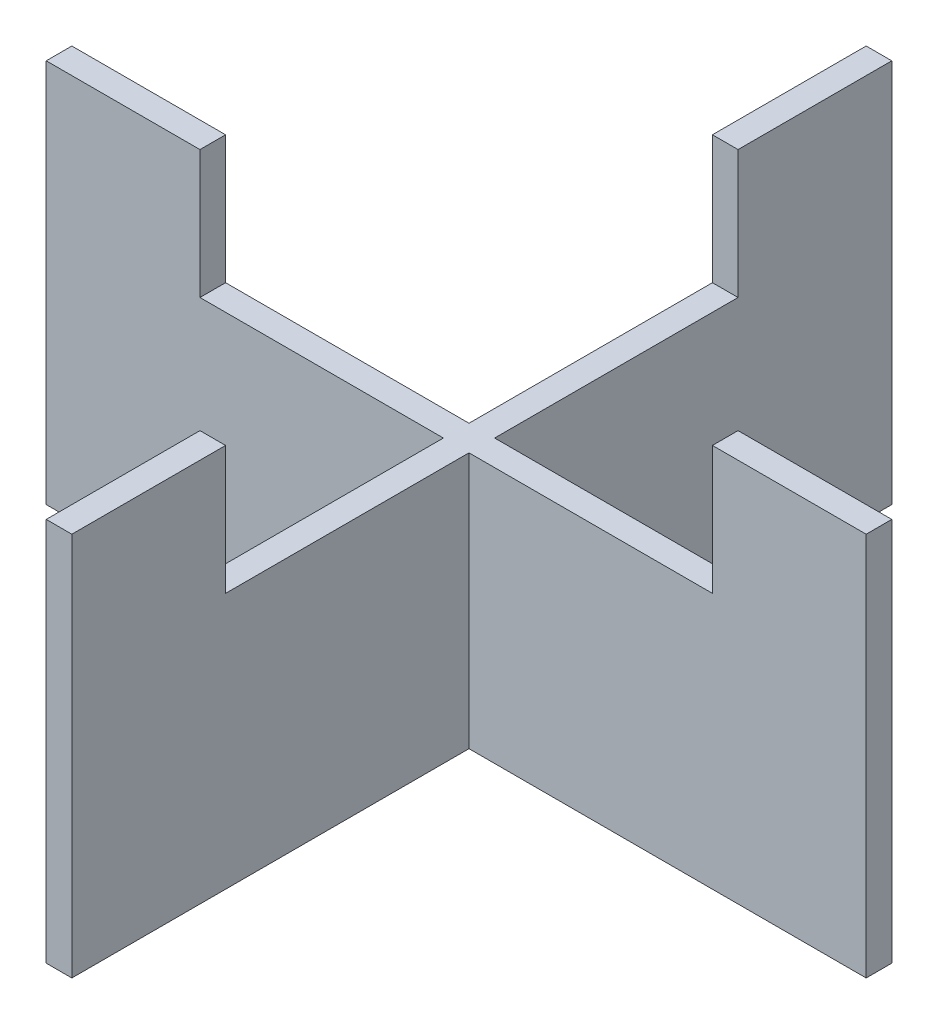
SolidWorks part; units mm, degrees
ref_plane "Alzado" through (0, 0, 0) normal (0, 0, 1) x (1, 0, 0)
ref_plane "Planta" through (0, 0, 0) normal (0, 1, 0) x (1, 0, 0)
ref_plane "Vista lateral" through (0, 0, 0) normal (1, 0, 0) x (0, 0, -1)
sketch "Croquis1" plane through (0, 0, 0) normal (0, 1, 0) x (1, 0, 0)
  line L0 (0, 0) -> (15.5, 0)
  line L1 (15.5, 0) -> (15.5, -15.5)
  line L2 (15.5, -15.5) -> (16.5, -15.5)
  line L3 (16.5, -15.5) -> (16.5, 0)
  line L4 (16.5, 0) -> (32, 0)
  line L5 (32, 0) -> (32, 1)
  line L6 (32, 1) -> (16.5, 1)
  line L7 (16.5, 1) -> (16.5, 16.5)
  line L8 (16.5, 16.5) -> (15.5, 16.5)
  line L9 (15.5, 16.5) -> (15.5, 1)
  line L10 (15.5, 1) -> (0, 1)
  line L11 (0, 1) -> (0, 0)
  dimension "D1" = 32
  dimension "D2" = 1
extrude "Saliente-Extruir1" add sketch "Croquis1" along normal blind 15
sketch "Croquis2" plane through (0, 15, 0) normal (0, 1, 0) x (1, 0, 0)
  line L0 (15.5, 1) -> (16.5, 0) construction
  line L2 (6, 10.5) -> (26, 10.5)
  line L3 (6, 10.5) -> (6, -9.5)
  line L4 (6, -9.5) -> (26, -9.5)
  line L5 (26, 10.5) -> (26, -9.5)
  line L6 (6, 10.5) -> (26, -9.5) construction
  line L7 (6, -9.5) -> (26, 10.5) construction
  point P4 (16, 0.5)
  dimension "D1" = 20
extrude "Cortar-Extruir1" cut sketch "Croquis2" against normal blind 5
